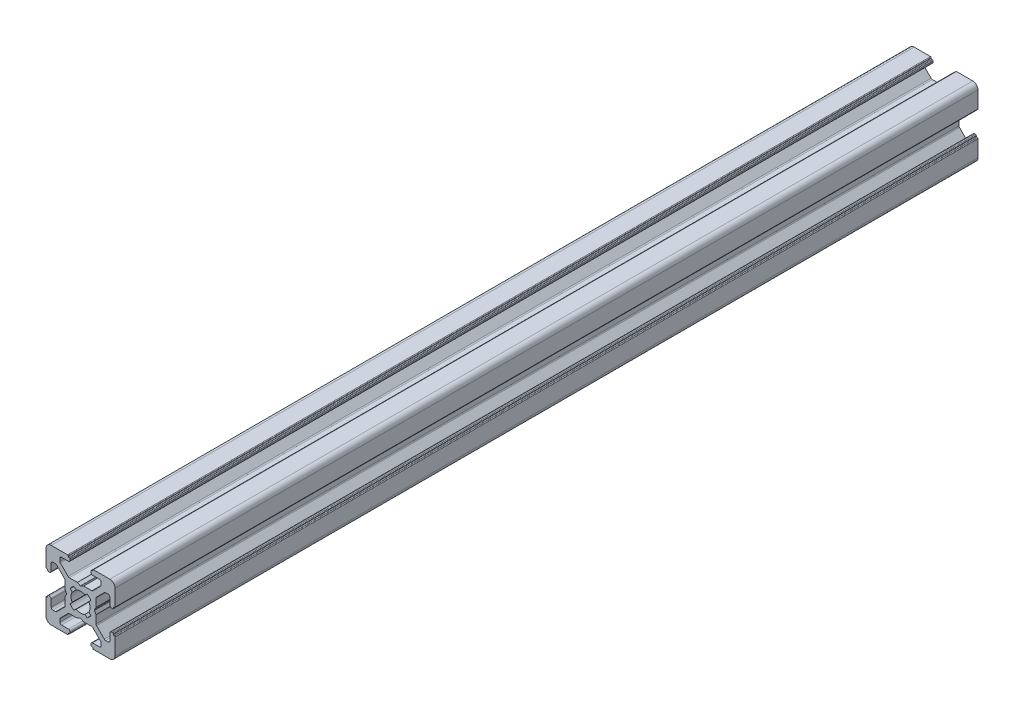
SolidWorks part; units mm, degrees
ref_plane "Front Plane" through (0, 0, 0) normal (0, 0, 1) x (1, 0, 0)
ref_plane "Top Plane" through (0, 0, 0) normal (0, 1, 0) x (1, 0, 0)
ref_plane "Right Plane" through (0, 0, 0) normal (1, 0, 0) x (0, 0, -1)
sketch "Sketch1" plane through (0, 0, 0) normal (0, 0, 1) x (1, 0, 0)
  line L0 (0, 13.3675) -> (0, -10.9159) construction
  line L1 (-12.9725, 0) -> (15.1887, 0) construction
  line L2 (-3.5, 8.5) -> (-5.5, 8.5)
  line L3 (-3.55, 9.7) -> (-3.55, 9.8)
  line L4 (-6, 7.2678) -> (-6, 8)
  line L5 (-7.2678, 6) -> (-8, 6)
  line L6 (-3.75, 10) -> (-8.5, 10)
  line L7 (-9.7, 3.55) -> (-9.8, 3.55)
  line L8 (-9.5, 3.2) -> (-9.5, 3.35)
  line L9 (-9, 3) -> (-9.3, 3)
  line L10 (-4.4732, 0.8536) -> (-4.0381, 0.1)
  line L11 (-4.5, 3.2322) -> (-4.5, 0.9536)
  line L12 (-8.5, 3.5) -> (-8.5, 5.5)
  line L13 (-10, 3.75) -> (-10, 8.5)
  line L14 (-3.5858, 4.6464) -> (-5.8536, 6.9142)
  line L15 (-4.6464, 3.5858) -> (-6.9142, 5.8536)
  line L16 (-3.2, 9.5) -> (-3.35, 9.5)
  line L17 (-3, 9) -> (-3, 9.3)
  line L18 (-0.8536, 4.4732) -> (-0.1, 4.0381)
  line L19 (-3.2322, 4.5) -> (-0.9536, 4.5)
  line L20 (-1.2582, 2.4453) -> (-1.9139, 2.9896)
  line L21 (-2.4453, 1.2582) -> (-2.9922, 1.9099)
  line L22 (3.5, -8.5) -> (5.5, -8.5)
  line L23 (3.55, -9.7) -> (3.55, -9.8)
  line L24 (6, -7.2678) -> (6, -8)
  line L25 (7.2678, -6) -> (8, -6)
  line L26 (3.75, -10) -> (8.5, -10)
  line L27 (9.7, -3.55) -> (9.8, -3.55)
  line L28 (9.5, -3.2) -> (9.5, -3.35)
  line L29 (9, -3) -> (9.3, -3)
  line L30 (4.4732, -0.8536) -> (4.0381, -0.1)
  line L31 (4.5, -3.2322) -> (4.5, -0.9536)
  line L32 (8.5, -3.5) -> (8.5, -5.5)
  line L33 (10, -3.75) -> (10, -8.5)
  line L34 (3.5858, -4.6464) -> (5.8536, -6.9142)
  line L35 (4.6464, -3.5858) -> (6.9142, -5.8536)
  line L36 (3.2, -9.5) -> (3.35, -9.5)
  line L37 (3, -9) -> (3, -9.3)
  line L38 (0.8536, -4.4732) -> (0.1, -4.0381)
  line L39 (3.2322, -4.5) -> (0.9536, -4.5)
  line L40 (1.2582, -2.4453) -> (1.9139, -2.9896)
  line L41 (2.4453, -1.2582) -> (2.9922, -1.9099)
  line L42 (-2.4453, -1.2582) -> (-2.9922, -1.9099)
  line L43 (-1.2582, -2.4453) -> (-1.9139, -2.9896)
  line L44 (-3.2322, -4.5) -> (-0.9536, -4.5)
  line L45 (-0.8536, -4.4732) -> (-0.1, -4.0381)
  line L46 (-3, -9) -> (-3, -9.3)
  line L47 (-3.2, -9.5) -> (-3.35, -9.5)
  line L48 (-4.6464, -3.5858) -> (-6.9142, -5.8536)
  line L49 (-3.5858, -4.6464) -> (-5.8536, -6.9142)
  line L50 (-10, -3.75) -> (-10, -8.5)
  line L51 (-8.5, -3.5) -> (-8.5, -5.5)
  line L52 (-4.5, -3.2322) -> (-4.5, -0.9536)
  line L53 (-4.4732, -0.8536) -> (-4.0381, -0.1)
  line L54 (-9, -3) -> (-9.3, -3)
  line L55 (-9.5, -3.2) -> (-9.5, -3.35)
  line L56 (-9.7, -3.55) -> (-9.8, -3.55)
  line L57 (2.4453, 1.2582) -> (2.9922, 1.9099)
  line L58 (1.2582, 2.4453) -> (1.9139, 2.9896)
  line L59 (3.2322, 4.5) -> (0.9536, 4.5)
  line L60 (0.8536, 4.4732) -> (0.1, 4.0381)
  line L61 (-3.75, -10) -> (-8.5, -10)
  line L62 (-7.2678, -6) -> (-8, -6)
  line L63 (-6, -7.2678) -> (-6, -8)
  line L64 (3, 9) -> (3, 9.3)
  line L65 (3.2, 9.5) -> (3.35, 9.5)
  line L66 (4.6464, 3.5858) -> (6.9142, 5.8536)
  line L67 (3.5858, 4.6464) -> (5.8536, 6.9142)
  line L68 (10, 3.75) -> (10, 8.5)
  line L69 (8.5, 3.5) -> (8.5, 5.5)
  line L70 (4.5, 3.2322) -> (4.5, 0.9536)
  line L71 (4.4732, 0.8536) -> (4.0381, 0.1)
  line L72 (9, 3) -> (9.3, 3)
  line L73 (9.5, 3.2) -> (9.5, 3.35)
  line L74 (9.7, 3.55) -> (9.8, 3.55)
  line L75 (3.75, 10) -> (8.5, 10)
  line L76 (7.2678, 6) -> (8, 6)
  line L77 (6, 7.2678) -> (6, 8)
  line L78 (3.55, 9.7) -> (3.55, 9.8)
  line L79 (3.5, 8.5) -> (5.5, 8.5)
  line L80 (-3.55, -9.7) -> (-3.55, -9.8)
  line L81 (-3.5, -8.5) -> (-5.5, -8.5)
  arc A0 (-10, 8.5) -> (-8.5, 10) centre (-8.5, 8.5) cw
  arc A1 (-8.5, 5.5) -> (-8, 6) centre (-8, 5.5) cw
  arc A2 (-7.2678, 6) -> (-6.9142, 5.8536) centre (-7.2678, 5.5) cw
  arc A3 (-5.8536, 6.9142) -> (-6, 7.2678) centre (-5.5, 7.2678) cw
  arc A4 (-6, 8) -> (-5.5, 8.5) centre (-5.5, 8) cw
  arc A5 (-9.7, 3.55) -> (-9.5, 3.35) centre (-9.7, 3.35) cw
  arc A6 (-9.8, 3.55) -> (-10, 3.75) centre (-9.8, 3.75) cw
  arc A7 (-9.3, 3) -> (-9.5, 3.2) centre (-9.3, 3.2) cw
  arc A8 (-8.5, 3.5) -> (-9, 3) centre (-9, 3.5) cw
  arc A9 (-4.6464, 3.5858) -> (-4.5, 3.2322) centre (-5, 3.2322) cw
  arc A10 (-4.4732, 0.8536) -> (-4.5, 0.9536) centre (-4.3, 0.9536) cw
  arc A11 (-4.0381, 0.1) -> (-4.0381, -0.1) centre (-4.2113, 0) cw
  arc A12 (-3.2, 9.5) -> (-3, 9.3) centre (-3.2, 9.3) cw
  arc A13 (-0.9536, 4.5) -> (-0.8536, 4.4732) centre (-0.9536, 4.3) cw
  arc A14 (-2.9922, 1.9099) -> (-1.9139, 2.9896) centre (0, 0) cw
  arc A15 (-3.2322, 4.5) -> (-3.5858, 4.6464) centre (-3.2322, 5) cw
  arc A16 (-3.75, 10) -> (-3.55, 9.8) centre (-3.75, 9.8) cw
  arc A17 (-3.35, 9.5) -> (-3.55, 9.7) centre (-3.35, 9.7) cw
  arc A18 (2.4453, -1.2582) -> (2.4453, 1.2582) centre (0, 0) ccw
  arc A19 (-3, 9) -> (-3.5, 8.5) centre (-3.5, 9) cw
  arc A20 (-2.4453, -1.2582) -> (-2.4453, 1.2582) centre (0, 0) cw
  arc A21 (10, -8.5) -> (8.5, -10) centre (8.5, -8.5) cw
  arc A22 (8.5, -5.5) -> (8, -6) centre (8, -5.5) cw
  arc A23 (7.2678, -6) -> (6.9142, -5.8536) centre (7.2678, -5.5) cw
  arc A24 (5.8536, -6.9142) -> (6, -7.2678) centre (5.5, -7.2678) cw
  arc A25 (6, -8) -> (5.5, -8.5) centre (5.5, -8) cw
  arc A26 (9.7, -3.55) -> (9.5, -3.35) centre (9.7, -3.35) cw
  arc A27 (9.8, -3.55) -> (10, -3.75) centre (9.8, -3.75) cw
  arc A28 (9.3, -3) -> (9.5, -3.2) centre (9.3, -3.2) cw
  arc A29 (8.5, -3.5) -> (9, -3) centre (9, -3.5) cw
  arc A30 (4.6464, -3.5858) -> (4.5, -3.2322) centre (5, -3.2322) cw
  arc A31 (4.4732, -0.8536) -> (4.5, -0.9536) centre (4.3, -0.9536) cw
  arc A32 (3.2, -9.5) -> (3, -9.3) centre (3.2, -9.3) cw
  arc A33 (-0.1, -4.0381) -> (0.1, -4.0381) centre (0, -4.2113) cw
  arc A34 (0.9536, -4.5) -> (0.8536, -4.4732) centre (0.9536, -4.3) cw
  arc A35 (2.9922, -1.9099) -> (1.9139, -2.9896) centre (0, 0) cw
  arc A36 (1.2582, -2.4453) -> (-1.2582, -2.4453) centre (0, 0) cw
  arc A37 (3.2322, -4.5) -> (3.5858, -4.6464) centre (3.2322, -5) cw
  arc A38 (3.75, -10) -> (3.55, -9.8) centre (3.75, -9.8) cw
  arc A39 (3.35, -9.5) -> (3.55, -9.7) centre (3.35, -9.7) cw
  arc A40 (3, -9) -> (3.5, -8.5) centre (3.5, -9) cw
  arc A41 (-3, -9) -> (-3.5, -8.5) centre (-3.5, -9) ccw
  arc A42 (-3.35, -9.5) -> (-3.55, -9.7) centre (-3.35, -9.7) ccw
  arc A43 (-3.75, -10) -> (-3.55, -9.8) centre (-3.75, -9.8) ccw
  arc A44 (-3.2322, -4.5) -> (-3.5858, -4.6464) centre (-3.2322, -5) ccw
  arc A45 (-2.9922, -1.9099) -> (-1.9139, -2.9896) centre (0, 0) ccw
  arc A46 (-0.9536, -4.5) -> (-0.8536, -4.4732) centre (-0.9536, -4.3) ccw
  arc A47 (-3.2, -9.5) -> (-3, -9.3) centre (-3.2, -9.3) ccw
  arc A48 (-4.4732, -0.8536) -> (-4.5, -0.9536) centre (-4.3, -0.9536) ccw
  arc A49 (3, 9) -> (3.5, 8.5) centre (3.5, 9) ccw
  arc A50 (3.35, 9.5) -> (3.55, 9.7) centre (3.35, 9.7) ccw
  arc A51 (3.75, 10) -> (3.55, 9.8) centre (3.75, 9.8) ccw
  arc A52 (3.2322, 4.5) -> (3.5858, 4.6464) centre (3.2322, 5) ccw
  arc A53 (1.2582, 2.4453) -> (-1.2582, 2.4453) centre (0, 0) ccw
  arc A54 (-4.6464, -3.5858) -> (-4.5, -3.2322) centre (-5, -3.2322) ccw
  arc A55 (-8.5, -3.5) -> (-9, -3) centre (-9, -3.5) ccw
  arc A56 (-9.3, -3) -> (-9.5, -3.2) centre (-9.3, -3.2) ccw
  arc A57 (-9.8, -3.55) -> (-10, -3.75) centre (-9.8, -3.75) ccw
  arc A58 (-9.7, -3.55) -> (-9.5, -3.35) centre (-9.7, -3.35) ccw
  arc A59 (-6, -8) -> (-5.5, -8.5) centre (-5.5, -8) ccw
  arc A60 (2.9922, 1.9099) -> (1.9139, 2.9896) centre (0, 0) ccw
  arc A61 (0.9536, 4.5) -> (0.8536, 4.4732) centre (0.9536, 4.3) ccw
  arc A62 (-0.1, 4.0381) -> (0.1, 4.0381) centre (0, 4.2113) ccw
  arc A63 (-5.8536, -6.9142) -> (-6, -7.2678) centre (-5.5, -7.2678) ccw
  arc A64 (-7.2678, -6) -> (-6.9142, -5.8536) centre (-7.2678, -5.5) ccw
  arc A65 (-8.5, -5.5) -> (-8, -6) centre (-8, -5.5) ccw
  arc A66 (-10, -8.5) -> (-8.5, -10) centre (-8.5, -8.5) ccw
  arc A67 (3.2, 9.5) -> (3, 9.3) centre (3.2, 9.3) ccw
  arc A68 (4.0381, 0.1) -> (4.0381, -0.1) centre (4.2113, 0) ccw
  arc A69 (4.4732, 0.8536) -> (4.5, 0.9536) centre (4.3, 0.9536) ccw
  arc A70 (4.6464, 3.5858) -> (4.5, 3.2322) centre (5, 3.2322) ccw
  arc A71 (8.5, 3.5) -> (9, 3) centre (9, 3.5) ccw
  arc A72 (9.3, 3) -> (9.5, 3.2) centre (9.3, 3.2) ccw
  arc A73 (9.8, 3.55) -> (10, 3.75) centre (9.8, 3.75) ccw
  arc A74 (9.7, 3.55) -> (9.5, 3.35) centre (9.7, 3.35) ccw
  arc A75 (6, 8) -> (5.5, 8.5) centre (5.5, 8) ccw
  arc A76 (5.8536, 6.9142) -> (6, 7.2678) centre (5.5, 7.2678) ccw
  arc A77 (7.2678, 6) -> (6.9142, 5.8536) centre (7.2678, 5.5) ccw
  arc A78 (8.5, 5.5) -> (8, 6) centre (8, 5.5) ccw
  arc A79 (10, 8.5) -> (8.5, 10) centre (8.5, 8.5) ccw
  dimension "D4" = 5.5
  dimension "D1" = 6
  dimension "D2" = 20
  dimension "D3" = 20
  dimension "D5" = 5.5
  dimension "D6" = 10
  dimension "D7" = 6
  dimension "D8" = 6
  dimension "D9" = 6
extrude "Extrude1" add sketch "Sketch1" along normal blind 250
